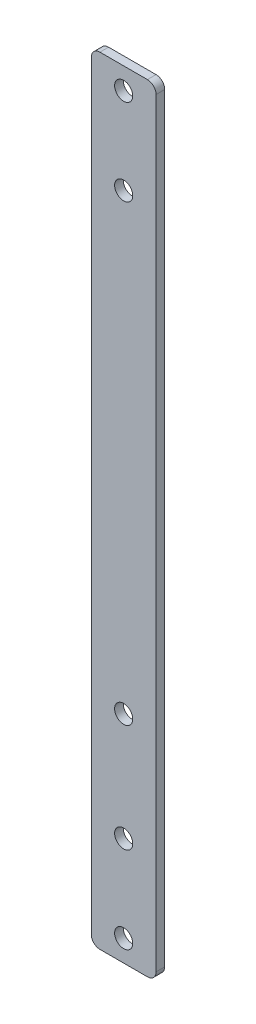
SolidWorks part; units mm, degrees
ref_plane "Спереди" through (0, 0, 0) normal (0, 0, 1) x (1, 0, 0)
ref_plane "Сверху" through (0, 0, 0) normal (0, 1, 0) x (1, 0, 0)
ref_plane "Справа" through (0, 0, 0) normal (1, 0, 0) x (0, 0, -1)
sketch "Эскиз1" plane through (0, 0, 0) normal (0, 0, 1) x (1, 0, 0)
  line L0 (0, 67.7129) -> (0, -93374.896) construction
  line L1 (-7.5, 173) -> (-7.5, -3)
  line L2 (7.5, 173) -> (7.5, -3)
  line L3 (-5.5, 175) -> (5.5, 175)
  line L4 (-5.5, -5) -> (5.5, -5)
  line L5 (12.2202, 85) -> (-12.0806, 85) construction
  circle A0 centre (0, 170) radius 2.1
  circle A1 centre (0, 150) radius 2.1
  circle A2 centre (0, 20) radius 2.1
  circle A3 centre (0, 0) radius 2.1
  arc A4 (5.5, -5) -> (7.5, -3) centre (5.5, -3) ccw
  arc A5 (-7.5, -3) -> (-5.5, -5) centre (-5.5, -3) ccw
  arc A6 (5.5, 175) -> (7.5, 173) centre (5.5, 173) cw
  arc A7 (-5.5, 175) -> (-7.5, 173) centre (-5.5, 173) ccw
  point P21 (7.5, -5)
  point P24 (-7.5, -5)
  point P27 (7.5, 175)
  point P30 (-7.5, 175)
  dimension "D3" = 4.2
  dimension "D4" = 4.2
  dimension "D7" = 2
  dimension "D1" = 180
  dimension "D2" = 15
  dimension "D5" = 20
  dimension "D6" = 5
extrude "Бобышка-Вытянуть1" add sketch "Эскиз1" along normal blind 2 contours A0 | A1 | A3 | A2 | L1 A5 L4 A4 L2 A6 L3 A7
sketch "Эскиз2" plane through (0, 0, 0) normal (0, 0, -1) x (-1, 0, 0)
  circle A0 centre (0, 130) radius 2.1
  circle A1 centre (0, 150) radius 2.1 construction
  dimension "D1" = 4.2
  dimension "D2" = 20
sketch "Эскиз3" plane through (0, 0, 2) normal (0, 0, 1) x (1, 0, 0)
  circle A0 centre (0, 45) radius 2.1
  circle A1 centre (0, 20) radius 2.1 construction
  dimension "D1" = 4.2
  dimension "D2" = 25
extrude "Вырез-Вытянуть2" cut sketch "Эскиз3" against normal blind 10
